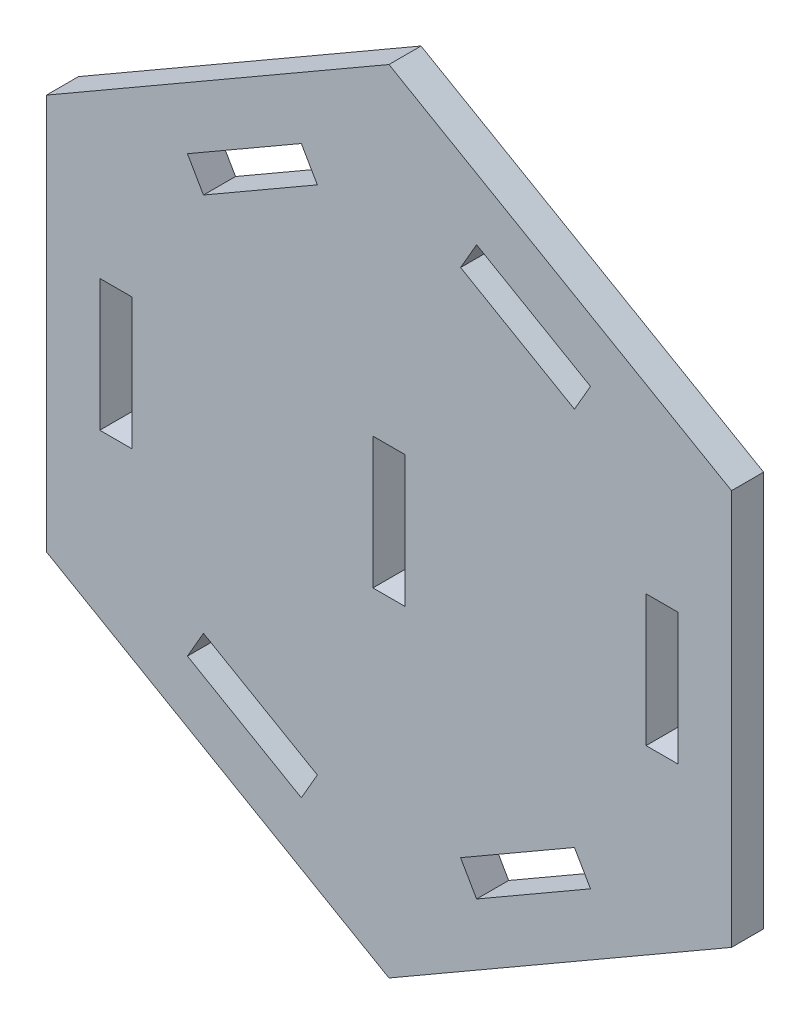
SolidWorks part; units mm, degrees
ref_plane "Alzado" through (0, 0, 0) normal (0, 0, 1) x (1, 0, 0)
ref_plane "Planta" through (0, 0, 0) normal (0, 1, 0) x (1, 0, 0)
ref_plane "Vista lateral" through (0, 0, 0) normal (1, 0, 0) x (0, 0, -1)
sketch "Croquis1" plane through (0, 0, 0) normal (0, 0, 1) x (1, 0, 0)
  line L0 (94, 227.5) -> (470, 227.5) construction
  line L45 (383.2081, 50.2174) -> (359.1586, 36.3324) construction
  line L49 (359.1586, 36.3324) -> (359.1586, 8.5624) construction
  line L50 (359.1586, 8.5624) -> (383.2081, -5.3226) construction
  line L51 (383.2081, -5.3226) -> (407.2576, 8.5624) construction
  line L76 (407.2576, 8.5624) -> (407.2576, 16.2974) construction
  line L77 (407.2576, 36.3324) -> (383.2081, 50.2174) construction
  line L78 (381.7081, 28.5974) -> (384.7081, 28.5974)
  line L79 (381.7081, 28.5974) -> (381.7081, 16.2974)
  line L80 (381.7081, 16.2974) -> (384.7081, 16.2974)
  line L81 (384.7081, 28.5974) -> (384.7081, 16.2974)
  line L82 (381.7081, 28.5974) -> (384.7081, 16.2974) construction
  line L83 (381.7081, 16.2974) -> (384.7081, 28.5974) construction
  line L84 (407.2576, 28.5974) -> (410.2576, 28.5974)
  line L85 (407.2576, 16.2974) -> (410.2576, 16.2974)
  line L86 (410.2576, 28.5974) -> (410.2576, 16.2974)
  line L87 (407.2576, 28.5974) -> (407.2576, 36.3324) construction
  line L88 (407.2576, 28.5974) -> (407.2576, 16.2974)
  line L89 (383.2081, 23.499) -> (383.2081, 21.0564) construction
  line L90 (359.1586, 16.2974) -> (356.1586, 16.2974)
  line L91 (356.1586, 28.5974) -> (356.1586, 16.2974)
  line L92 (359.1586, 28.5974) -> (356.1586, 28.5974)
  line L93 (359.1586, 28.5974) -> (359.1586, 16.2974)
  line L94 (389.9068, 46.3499) -> (400.5589, 40.1999)
  line L95 (389.9068, 46.3499) -> (391.4068, 48.948)
  line L96 (400.5589, 40.1999) -> (402.0589, 42.798)
  line L97 (391.4068, 48.948) -> (402.0589, 42.798)
  line L98 (383.2081, 53.5116) -> (383.2081, 44.0492) construction
  line L99 (381.1632, 22.4474) -> (385.7524, 22.4474) construction
  line L100 (365.8573, 40.1999) -> (364.3573, 42.798)
  line L101 (375.0094, 48.948) -> (364.3573, 42.798)
  line L102 (376.5094, 46.3499) -> (375.0094, 48.948)
  line L103 (376.5094, 46.3499) -> (365.8573, 40.1999)
  line L104 (376.5094, -1.4551) -> (365.8573, 4.6949)
  line L105 (376.5094, -1.4551) -> (375.0094, -4.0532)
  line L106 (375.0094, -4.0532) -> (364.3573, 2.0968)
  line L107 (365.8573, 4.6949) -> (364.3573, 2.0968)
  line L108 (400.5589, 4.6949) -> (402.0589, 2.0968)
  line L109 (391.4068, -4.0532) -> (402.0589, 2.0968)
  line L110 (389.9068, -1.4551) -> (391.4068, -4.0532)
  line L111 (389.9068, -1.4551) -> (400.5589, 4.6949)
  line L116 (383.2081, -14.5526) -> (415.251, 3.9474)
  line L117 (415.251, 3.9474) -> (415.251, 40.9474)
  line L118 (415.251, 40.9474) -> (383.2081, 59.4474)
  line L119 (383.2081, 59.4474) -> (351.1652, 40.9474)
  line L120 (351.1652, 40.9474) -> (351.1652, 3.9474)
  line L121 (351.1652, 3.9474) -> (383.2081, -14.5526)
  circle A2 centre (383.2081, 22.4474) radius 24.0495 construction
  circle A3 centre (383.2081, 22.4474) radius 32.0429 construction
  dimension "D1" = 37
extrude "Saliente-Extruir1" add sketch "Croquis1" along normal blind 3
